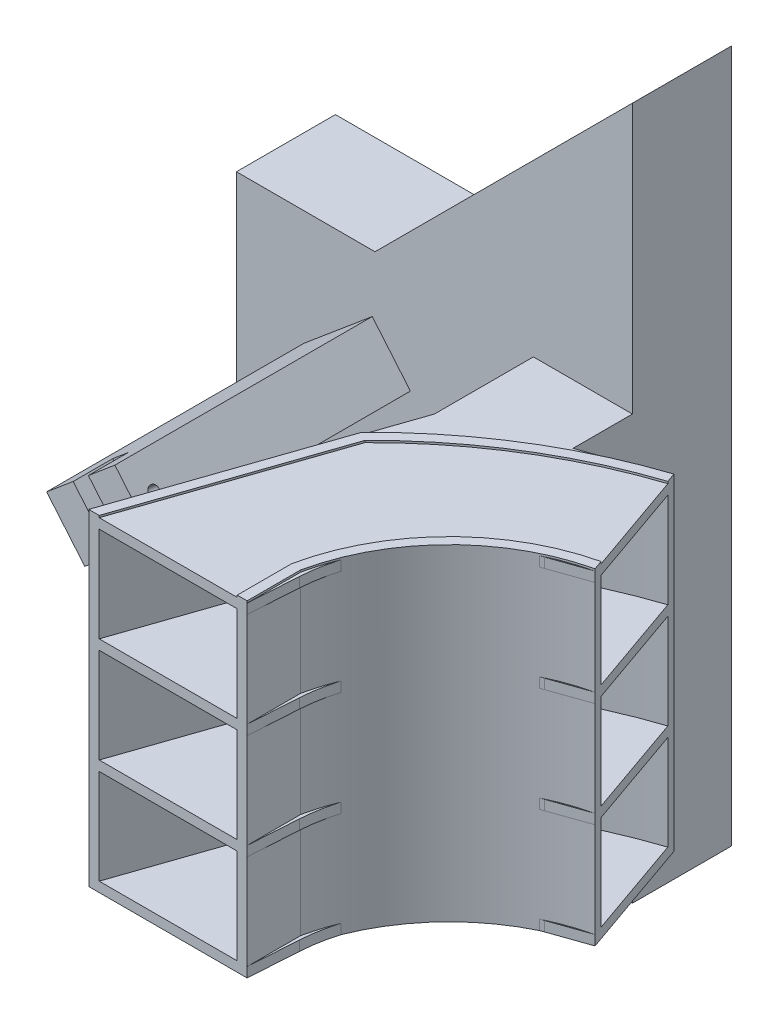
SolidWorks part; units mm, degrees
ref_plane "Přední rovina" through (0, 0, 0) normal (0, 0, 1) x (1, 0, 0)
ref_plane "Horní rovina" through (0, 0, 0) normal (0, 1, 0) x (1, 0, 0)
ref_plane "Pravá rovina" through (0, 0, 0) normal (1, 0, 0) x (0, 0, -1)
sketch "Skica1" plane through (0, 0, 0) normal (0, 0, 1) x (1, 0, 0)
  line L0 (0, 0) -> (200, 0)
  line L1 (200, 0) -> (200, 350)
  line L2 (200, 350) -> (70, 220)
  line L3 (70, 220) -> (0, 220)
  line L4 (0, 220) -> (0, 0)
  dimension "D1" = 350
  dimension "D2" = 200
  dimension "D3" = 70
  dimension "D4" = 220
extrude "Přidat vysunutím1" add sketch "Skica1" along normal blind 50
sketch "Skica7" plane through (0, 0, 50) normal (0, 0, 1) x (1, 0, 0)
  line L1 (150, 50) -> (200, 50)
  line L2 (150, 50) -> (150, 214)
  line L3 (150, 214) -> (200, 214)
  line L4 (200, 50) -> (200, 214)
  line L7 (200, 0) -> (200, 350) construction
  line L8 (0, 0) -> (200, 0) construction
  dimension "D1" = 164
  dimension "D2" = 50
  dimension "D3" = 50
extrude "Přidat vysunutím5" add sketch "Skica7" along normal blind 30
sketch "Skica23" plane through (0, 50, 0) normal (0, -1, 0) x (1, 0, 0)
  line L0 (200, 80) -> (237.7504, 66.7748)
  line L1 (237.7504, 66.7748) -> (259.2414, 128.1192)
  line L2 (259.2414, 128.1192) -> (240.3662, 134.7318)
  line L3 (186.9773, 205.1649) -> (185.4009, 230)
  line L4 (185.4009, 230) -> (105.4009, 230)
  line L5 (105.4009, 230) -> (150, 100)
  line L6 (150, 100) -> (150, 80)
  line L7 (150, 80) -> (200, 80)
  arc A0 (240.3662, 134.7318) -> (186.9773, 205.1649) centre (266.8166, 210.2326) cw
  dimension "D1" = 80
  dimension "D2" = 65
  dimension "D3" = 80
  dimension "D4" = 20
  dimension "D5" = 40
  dimension "D6" = 20
  dimension "D7" = 130
  dimension "D8" = 160.693
  dimension "D9" = 50
  dimension "D10" = 137.4375
extrude "Přidat vysunutím16" add sketch "Skica23" against normal blind 5
pattern_linear "LinPole1" count 4 spacing 53 along (0, 1, 0) of "Přidat vysunutím16"
sketch "Skica26" plane through (0, 50, 0) normal (0, -1, 0) x (1, 0, 0)
  line L0 (105.4009, 230) -> (150, 100) construction
  line L1 (140.6066, 127.3803) -> (105.4009, 230)
  line L2 (239.4036, 71.4936) -> (237.7504, 66.7748)
  line L3 (185.4009, 230) -> (185.4009, 202.9284)
  line L4 (185.4009, 230) -> (105.4009, 230) construction
  line L5 (110.687, 230) -> (144.9703, 130.0691)
  line L6 (237.7504, 66.7748) -> (259.2414, 128.1192) construction
  line L7 (185.4009, 230) -> (180.4009, 230)
  line L8 (180.4009, 230) -> (180.4009, 202.5427)
  line L9 (257.5882, 123.4004) -> (259.2414, 128.1192)
  line L10 (110.687, 230) -> (105.4009, 230)
  arc A0 (237.7504, 66.7748) -> (140.6066, 127.3803) centre (312.7197, 295.1) cw
  arc A1 (185.4009, 202.9284) -> (259.2414, 128.1192) centre (281.2141, 223.6542) ccw
  arc A2 (144.9703, 130.0691) -> (239.4036, 71.4936) centre (312.7197, 295.1) ccw
  arc A3 (180.4009, 202.5427) -> (257.5882, 123.4004) centre (281.2141, 223.6542) ccw
  dimension "D4" = 103
  dimension "D5" = 98.0292
  dimension "D7" = 235.3191
  dimension "D8" = 240.3181
  dimension "D1" = 5
  dimension "D2" = 5
  dimension "D3" = 5
  dimension "D6" = 5
extrude "Přidat vysunutím17" add sketch "Skica26" against normal blind 55
pattern_linear "LinPole2" count 3 spacing 55 along (0, 1, 0) of "Přidat vysunutím17"
sketch "Skica27" plane through (0, 0, 50) normal (0, 0, 1) x (1, 0, 0)
  line L0 (53.4058, 139.0466) -> (87.8778, 167.9721)
  line L1 (53.4058, 139.0466) -> (34.1222, 162.0279)
  line L2 (87.8778, 167.9721) -> (68.5942, 190.9534)
  line L3 (34.1222, 162.0279) -> (68.5942, 190.9534)
  line L4 (53.4058, 139.0466) -> (68.5942, 190.9534) construction
  line L5 (87.8778, 167.9721) -> (34.1222, 162.0279) construction
  line L6 (0, 220) -> (0, 0) construction
  line L7 (70, 220) -> (0, 220) construction
  point P0 (61.1461, 164.3972)
  point P1 (61, 165)
  dimension "D1" = 45
  dimension "D2" = 30
  dimension "D3" = 61
  dimension "D4" = 55
  dimension "D5" = 130
extrude "Přidat vysunutím18" add sketch "Skica27" along normal blind 110
sketch "Skica28" plane through (0, 0, 160) normal (0, 0, 1) x (1, 0, 0)
  line L0 (55.1884, 179.7046) -> (74.472, 156.7233)
  line L1 (68.5942, 190.9534) -> (34.1222, 162.0279) construction
  line L2 (53.4058, 139.0466) -> (87.8778, 167.9721) construction
  line L3 (47.528, 173.2767) -> (66.8116, 150.2954)
  line L4 (68.5942, 190.9534) -> (34.1222, 162.0279) construction
  line L5 (34.1222, 162.0279) -> (53.4058, 139.0466) construction
  line L6 (87.8778, 167.9721) -> (68.5942, 190.9534) construction
  line L7 (55.1884, 179.7046) -> (68.5942, 190.9534)
  line L8 (68.5942, 190.9534) -> (87.8778, 167.9721)
  line L9 (87.8778, 167.9721) -> (74.472, 156.7233)
  line L10 (47.528, 173.2767) -> (34.1222, 162.0279)
  line L11 (34.1222, 162.0279) -> (53.4058, 139.0466)
  line L12 (53.4058, 139.0466) -> (66.8116, 150.2954)
  dimension "D1" = 17.5
  dimension "D2" = 17.5
extrude "Přidat vysunutím19" add sketch "Skica28" along normal blind 20
sketch "Skica29" plane through (99.8069, 83.7479, 0) normal (-0.766, -0.6428, 0) x (0, 0, 1)
  line L0 (180, 102.1873) -> (180, 72.1873) construction
  line L1 (180, 102.1873) -> (50, 102.1873) construction
  circle A0 centre (170, 87.1873) radius 2.5
  dimension "D3" = 5
  dimension "D1" = 10
  dimension "D2" = 15
extrude "Odebrat vysunutím1" cut sketch "Skica29" against normal through all
